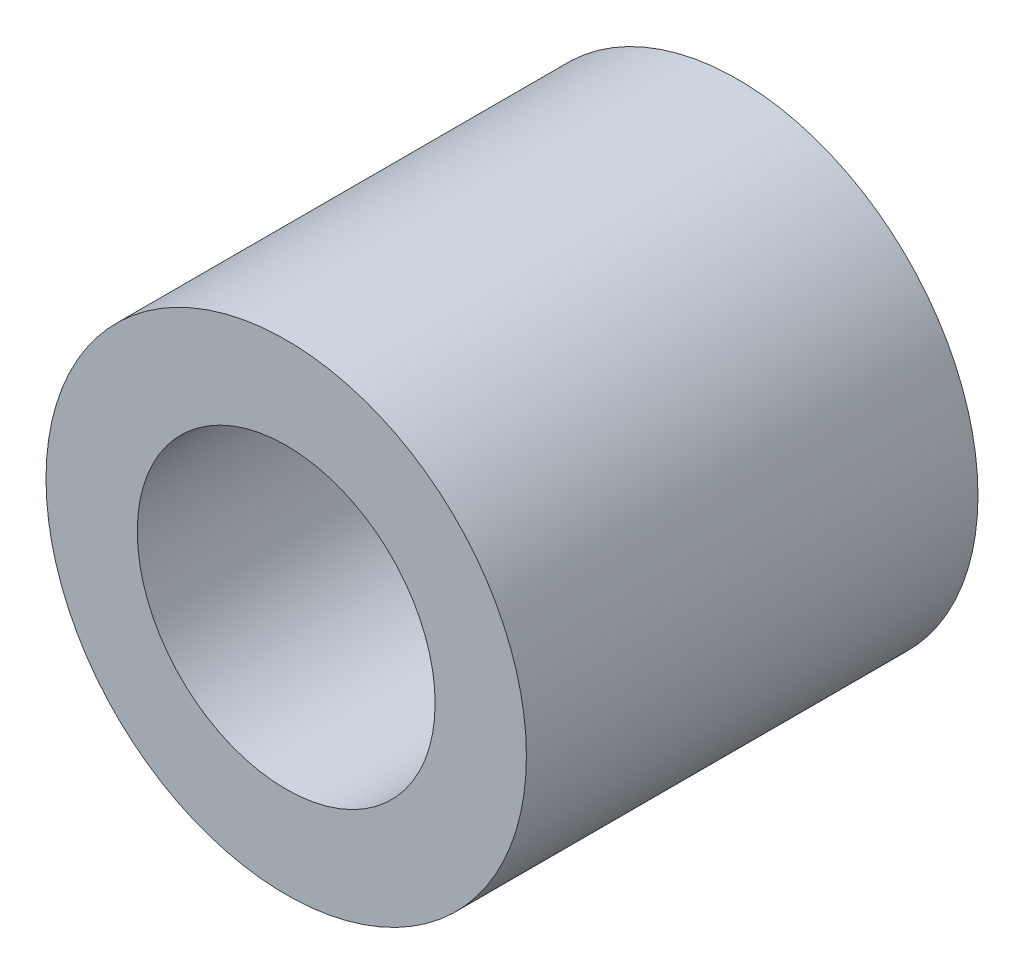
SolidWorks part; units mm, degrees
ref_plane "Plan de face" through (0, 0, 0) normal (0, 0, 1) x (1, 0, 0)
ref_plane "Plan de dessus" through (0, 0, 0) normal (0, 1, 0) x (1, 0, 0)
ref_plane "Plan de droite" through (0, 0, 0) normal (1, 0, 0) x (0, 0, -1)
sketch "Esquisse1" plane through (0, 0, 0) normal (0, 0, 1) x (1, 0, 0)
  circle A0 centre (0, 0) radius 2.5
  circle A1 centre (0, 0) radius 1.55
  dimension "D1" = 5
  dimension "D2" = 3.1
extrude "Boss.-Extru.1" add sketch "Esquisse1" along normal blind 4.7
